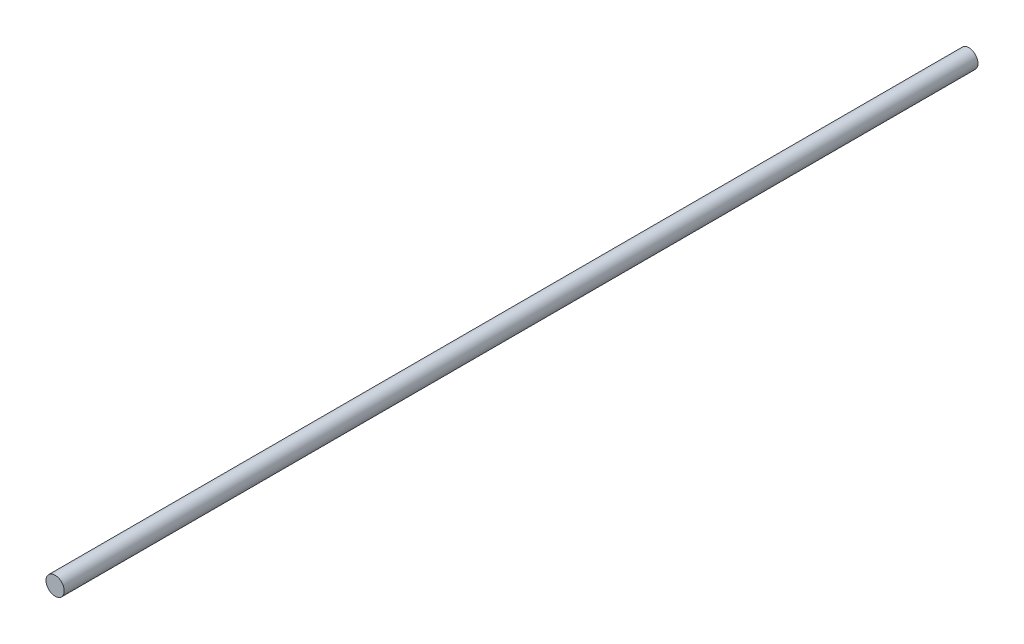
SolidWorks part; units mm, degrees
material "Обычная углеродистая сталь"
ref_plane "Спереди" through (0, 0, 0) normal (0, 0, 1) x (1, 0, 0)
ref_plane "Сверху" through (0, 0, 0) normal (0, 1, 0) x (1, 0, 0)
ref_plane "Справа" through (0, 0, 0) normal (1, 0, 0) x (0, 0, -1)
sketch "Эскиз1" plane through (0, 0, 0) normal (0, 1, 0) x (1, 0, 0)
  line L0 (3.4, 0) -> (0, 0)
  line L1 (0, 0) -> (0, -340)
  line L2 (0, -340) -> (3.4, -340)
  line L3 (3.4, -340) -> (3.4, 0)
  line L4 (0, 0) -> (0, -340) construction
revolve "Повернуть1" add sketch "Эскиз1" angle 360 about L4
